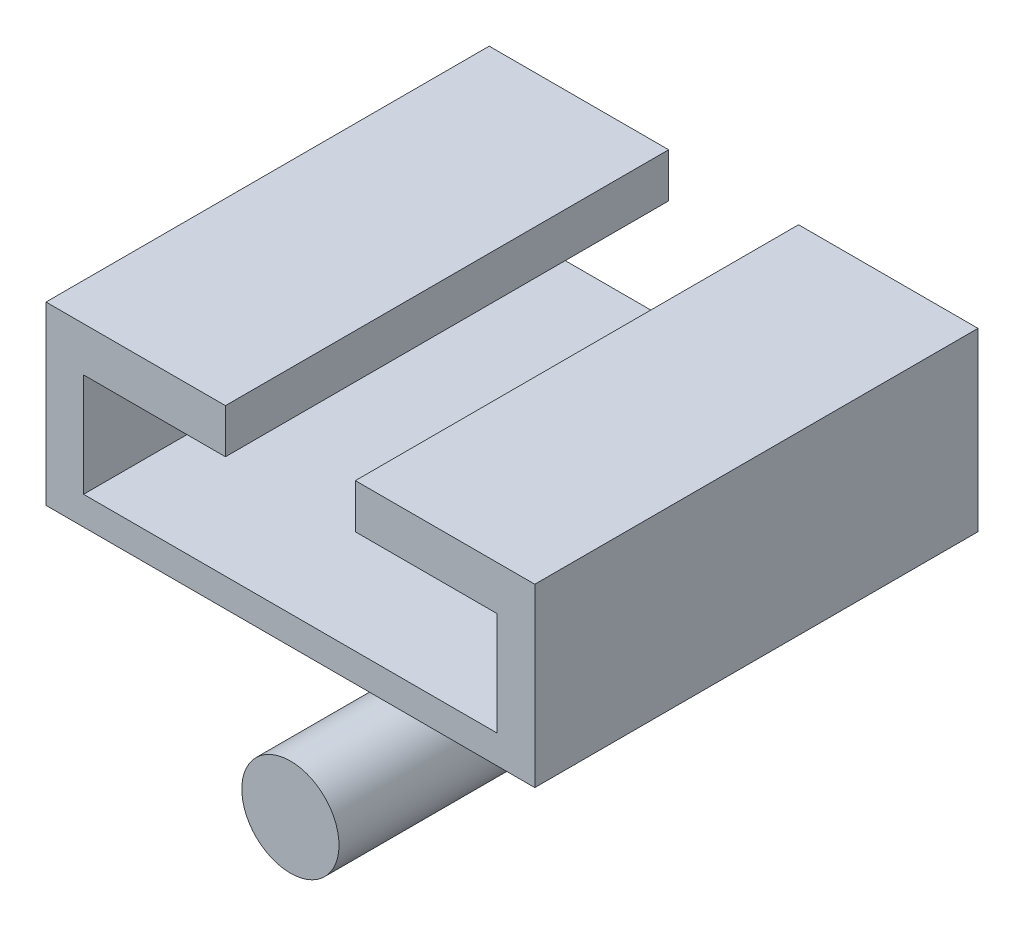
SolidWorks part; units mm, degrees
material "ASTM A36 Steel"
ref_plane "Front Plane" through (0, 0, 0) normal (0, 0, 1) x (1, 0, 0)
ref_plane "Top Plane" through (0, 0, 0) normal (0, 1, 0) x (1, 0, 0)
ref_plane "Right Plane" through (0, 0, 0) normal (1, 0, 0) x (0, 0, -1)
sketch "Sketch1" plane through (0, 0, 0) normal (0, 0, 1) x (1, 0, 0)
  line L1 (0, 0) -> (84.0404, 0)
  line L2 (0, 0) -> (0, 30.284)
  line L3 (0, 30.284) -> (84.0404, 30.284)
  line L4 (84.0404, 0) -> (84.0404, 30.284)
extrude "Boss-Extrude1" add sketch "Sketch1" against normal blind 76.2
sketch "Sketch2" plane through (0, 0, 0) normal (0, 0, 1) x (1, 0, 0)
  line L0 (30.853, 30.284) -> (53.1874, 30.284)
  line L1 (84.0404, 30.284) -> (0, 30.284) construction
  line L2 (53.1874, 30.284) -> (53.1874, 22.664)
  line L3 (53.1874, 22.664) -> (77.5802, 22.664)
  line L4 (77.5802, 22.664) -> (77.5802, 4.884)
  line L5 (0, 0) -> (84.0404, 0) construction
  line L6 (77.5802, 4.884) -> (6.4602, 4.884)
  line L7 (42.0202, 30.284) -> (42.0202, 43.5983) construction
  line L8 (6.4602, 22.664) -> (6.4602, 4.884)
  line L9 (30.853, 22.664) -> (6.4602, 22.664)
  line L10 (30.853, 30.284) -> (30.853, 22.664)
  point P13 (42.0202, 0)
  point P16 (42.0202, 30.284)
  dimension "D1" = 25.4
  dimension "D2" = 7.62
  dimension "D3" = 35.56
extrude "Cut-Extrude1" cut sketch "Sketch2" against normal through all
ref_plane "Plane1" through (0, 0, -76.2) normal (0, 0, 1) x (1, 0, 0)
sketch "Sketch3" plane through (0, 0, -76.2) normal (0, 0, 1) x (1, 0, 0)
  line L0 (33.6617, 0) -> (50.3787, 0)
  line L1 (0, 0) -> (84.0404, 0) construction
  line L2 (50.3787, 0) -> (50.3787, -25.4)
  line L3 (50.3787, -25.4) -> (33.6617, -25.4)
  line L4 (42.0202, 0) -> (42.0202, 37.7132) construction
  line L5 (33.6617, 0) -> (33.6617, -25.4)
  point P9 (42.0202, -25.4)
  point P10 (42.0202, 0)
  dimension "D1" = 25.4
extrude "Boss-Extrude2" add sketch "Sketch3" along normal blind 6.35
sketch "Sketch4" plane through (0, 0, -76.2) normal (0, 0, 1) x (1, 0, 0)
  line L0 (33.6617, -25.4) -> (50.3787, -25.4) construction
  circle A0 centre (42.0202, -25.4) radius 8.3585
extrude "Boss-Extrude3" add sketch "Sketch4" along normal blind 76.2
